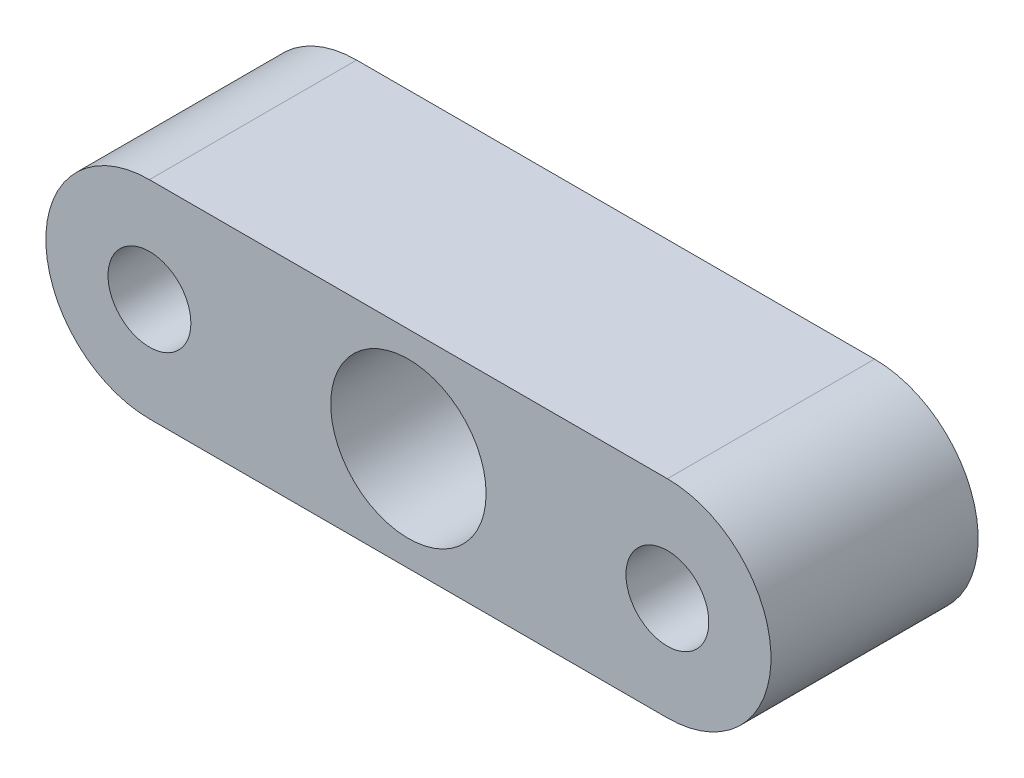
SolidWorks part; units mm, degrees
ref_plane "前视基准面" through (0, 0, 0) normal (0, 0, 1) x (1, 0, 0)
ref_plane "上视基准面" through (0, 0, 0) normal (0, 1, 0) x (1, 0, 0)
ref_plane "右视基准面" through (0, 0, 0) normal (1, 0, 0) x (0, 0, -1)
sketch "草图1" plane through (0, 0, 0) normal (0, 0, 1) x (1, 0, 0)
  line L0 (0, 0) -> (0, 21.7828) construction
  line L1 (0, 0) -> (-51.1785, 0) construction
  line L2 (-51.1785, 0) -> (33.4607, 0) construction
  line L3 (-25, 0) -> (25, 0) construction
  line L4 (-25, 10) -> (25, 10)
  line L5 (-25, -10) -> (25, -10)
  circle A0 centre (0, 0) radius 7.5
  circle A1 centre (-25, 0) radius 4
  circle A2 centre (25, 0) radius 4
  arc A3 (-25, 10) -> (-25, -10) centre (-25, 0) ccw
  arc A4 (25, -10) -> (25, 10) centre (25, 0) ccw
  point P12 (0, 0)
  dimension "D1" = 15
  dimension "D2" = 25
  dimension "D4" = 10
  dimension "D3" = 50
extrude "凸台-拉伸1" add sketch "草图1" along normal blind 20
